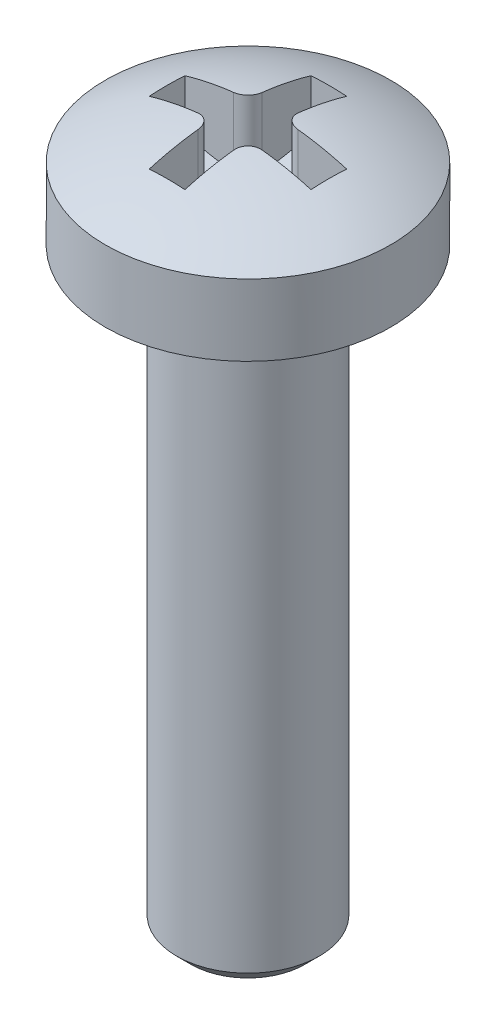
SolidWorks part; units mm, degrees
material "Cast Stainless Steel"
ref_plane "Front Plane" through (0, 0, 0) normal (0, 0, 1) x (1, 0, 0)
ref_plane "Top Plane" through (0, 0, 0) normal (0, 1, 0) x (1, 0, 0)
ref_plane "Right Plane" through (0, 0, 0) normal (1, 0, 0) x (0, 0, -1)
sketch "Sketch1" plane through (0, 0, 0) normal (0, 0, 1) x (1, 0, 0)
  line L0 (0, 0) -> (0, 4.6)
  line L1 (0, 4.6) -> (0, -22.0705) construction
  line L2 (6, 3) -> (6, 0)
  line L3 (6, 0) -> (3, 0)
  line L4 (3, 0) -> (3, -25)
  line L5 (3, -25) -> (0, -25)
  line L6 (0, -25) -> (0, 0)
  arc A0 (0, 4.6) -> (6, 3) centre (0, -7.45) cw
  dimension "D2" = 6
  dimension "D3" = 12
  dimension "D1" = 3
  dimension "D4" = 4.6
  dimension "D5" = 25
revolve "Revolve1" add sketch "Sketch1" angle 360 about L1
sketch "Sketch3" plane through (0, 0, 0) normal (0, 0, 1) x (1, 0, 0)
  line L0 (6, 1.5) -> (-6, 1.5) construction
  line L1 (6, 0) -> (6, 3) construction
  line L2 (-6, 3) -> (-6, 0) construction
  line L3 (0, 0) -> (0, 1.5) construction
  arc A0 (0, 1.5) -> (6, 3) centre (0, 14.25) ccw
  point P3 (0, 1.5)
surface "Surface-Revolve1" sketch "Sketch3" parameters "D1"=360
sketch "Sketch4" plane through (0, 0, 0) normal (0, 1, 0) x (1, 0, 0)
  line L0 (-0.75, -0.75) -> (-0.75, -3.4)
  line L1 (-3.4, 0.75) -> (-0.75, 0.75)
  line L2 (-3.4, 0.75) -> (-3.4, -0.75)
  line L3 (-3.4, -0.75) -> (-0.75, -0.75)
  line L4 (3.4, 0.75) -> (3.4, -0.75)
  line L5 (-3.4, 0.75) -> (3.4, -0.75) construction
  line L6 (-3.4, -0.75) -> (3.4, 0.75) construction
  line L7 (-0.75, 3.4) -> (0.75, 3.4)
  line L8 (-0.75, 3.4) -> (-0.75, 0.75)
  line L9 (-0.75, -3.4) -> (0.75, -3.4)
  line L10 (0.75, 3.4) -> (0.75, 0.75)
  line L11 (-0.75, 3.4) -> (0.75, -3.4) construction
  line L12 (-0.75, -3.4) -> (0.75, 3.4) construction
  line L13 (0.75, 0.75) -> (3.4, 0.75)
  line L14 (0.75, -0.75) -> (0.75, -3.4)
  line L15 (0.75, -0.75) -> (3.4, -0.75)
  point P0 (0, 0)
  point P6 (0, 0)
  dimension "D3" = 1.5
  dimension "D4" = 1.5
  dimension "D1" = 6.8
  dimension "D2" = 6.8
extrude "Cut-Extrude1" cut sketch "Sketch4" against normal up to surface (18.0154 mm away) from offset 20
delete or keep bodies "Body-Delete/Keep 1" type delete bodies bodies 102
fillet "Fillet1" radius 0.6 4 edges at (0.75, 3.0487, -0.75) (0.75, 3.0487, 0.75) (-0.75, 3.0487, 0.75) (-0.75, 3.0487, -0.75)
chamfer "Chamfer1" distance 0.6 angle 45 1 edges at (0, -25, 3)
equation "\"d1\"= 6"
equation "\"d2\"= \"d1\" * 2"
equation "\"k\"= 4.6"
equation "\"v\"= 3"
equation "\"D1@Sketch1\"=\"v\""
equation "\"D3@Sketch1\"=\"d2\""
equation "\"D2@Sketch1\"= \"d1\""
equation "\"D4@Sketch1\"=\"k\""
equation "\"L\"= 25"
equation "\"D5@Sketch1\"=\"L\""
equation "\"D1@Sketch4\"=\"m\""
equation "\"D2@Sketch4\"=\"m\""
equation "\"D3@Sketch4\" = \"d1\" / 4"
equation "\"D4@Sketch4\" = \"d1\" / 4"
equation "\"D1@Fillet1\"=\"d1\"/10"
equation "\"D1@Chamfer1\"=\"d1\"/10"
equation "\"m\"= 6.8"
